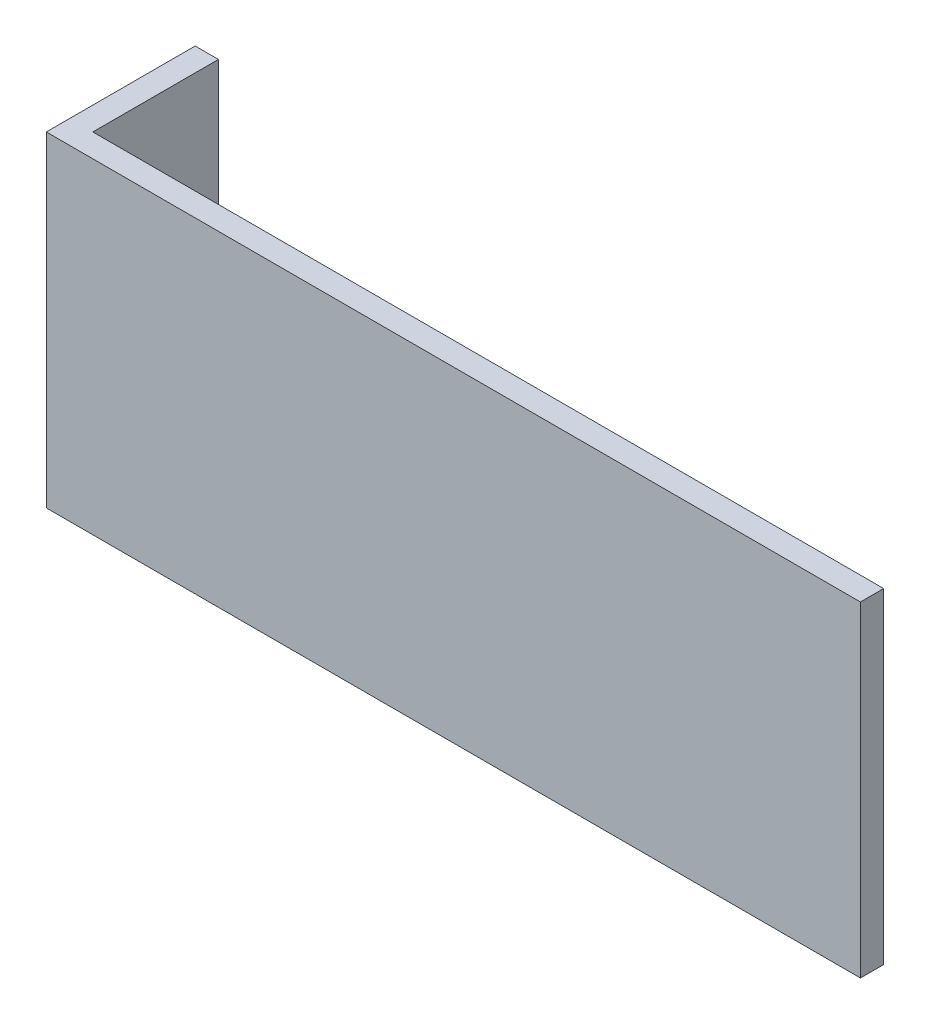
SolidWorks part; units mm, degrees
ref_plane "Front Plane" through (0, 0, 0) normal (0, 0, 1) x (1, 0, 0)
ref_plane "Top Plane" through (0, 0, 0) normal (0, 1, 0) x (1, 0, 0)
ref_plane "Right Plane" through (0, 0, 0) normal (1, 0, 0) x (0, 0, -1)
sketch "Sketch2" plane through (0, 0, 0) normal (0, 1, 0) x (1, 0, 0)
  line L1 (0, 0) -> (170, 0)
  line L2 (0, 0) -> (0, 5)
  line L3 (0, 5) -> (170, 5)
  line L4 (170, 0) -> (170, 5)
  line L5 (0, 0) -> (-5, 0)
  line L6 (0, 0) -> (0, 32)
  line L7 (0, 32) -> (-5, 32)
  line L8 (-5, 0) -> (-5, 32)
  dimension "D1" = 170
  dimension "D2" = 5
  dimension "D3" = 32
extrude "Boss-Extrude1" add sketch "Sketch2" along normal blind 70 contours L6 L5 L8 L7 | L2 L1 L4 L3
